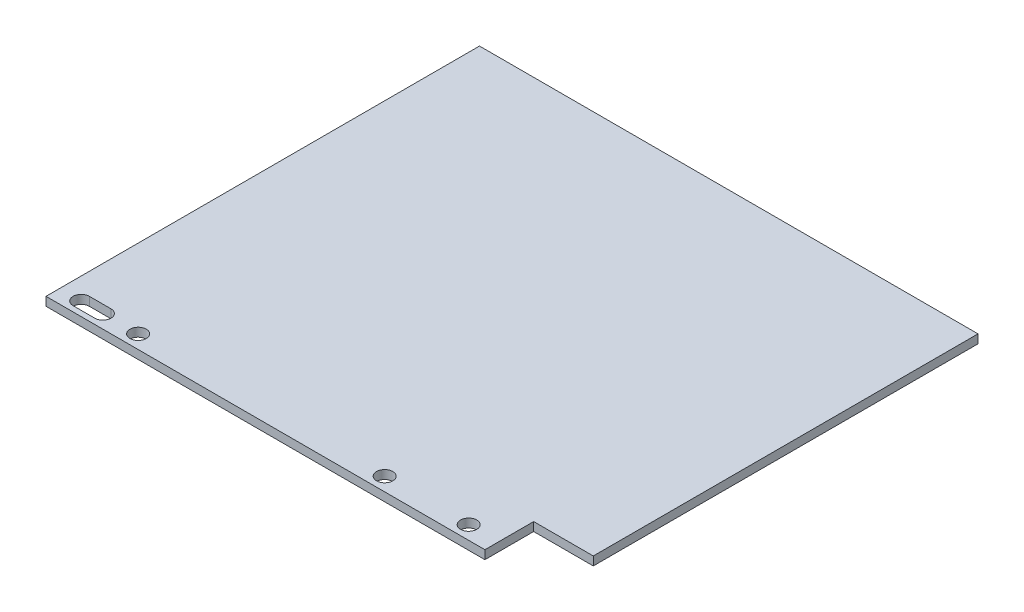
SolidWorks part; units mm, degrees
material "C-Glass Fiber"
ref_plane "Front Plane" through (0, 0, 0) normal (0, 0, 1) x (1, 0, 0)
ref_plane "Top Plane" through (0, 0, 0) normal (0, 1, 0) x (1, 0, 0)
ref_plane "Right Plane" through (0, 0, 0) normal (1, 0, 0) x (0, 0, -1)
sketch "Sketch1" plane through (0, 0, 0) normal (0, 1, 0) x (1, 0, 0)
  line L0 (46, -28.8083) -> (35, -28.8083)
  line L1 (35, -37.8083) -> (-46, -37.8083)
  line L2 (46, -28.8083) -> (46, 42.1917)
  line L3 (46, 42.1917) -> (-46, 42.1917)
  line L4 (-46, -37.8083) -> (-46, 42.1917)
  line L5 (35, -28.8083) -> (35, -37.8083)
  line L6 (-38, -35.3083) -> (-42, -35.3083) construction
  line L7 (-38, -36.8083) -> (-42, -36.8083)
  line L8 (-38, -33.8083) -> (-42, -33.8083)
  circle A0 centre (29.5, -35.3083) radius 1.5
  circle A1 centre (14, -35.3083) radius 1.5
  circle A2 centre (-31.5, -35.3083) radius 1.5
  arc A3 (-38, -36.8083) -> (-38, -33.8083) centre (-38, -35.3083) ccw
  arc A4 (-42, -33.8083) -> (-42, -36.8083) centre (-42, -35.3083) ccw
  point P0 (0, 0)
  point P16 (-40, -35.3083)
  dimension "D5" = 2.5
  dimension "D1" = 92
  dimension "D2" = 80
  dimension "D3" = 9
  dimension "D4" = 11
  dimension "D6" = 75.5
  dimension "D7" = 60
  dimension "D8" = 14.5
  dimension "D9" = 6
  dimension "D10" = 4
  dimension "D11" = 3
extrude "Boss-Extrude1" add sketch "Sketch1" along normal blind 1.6
